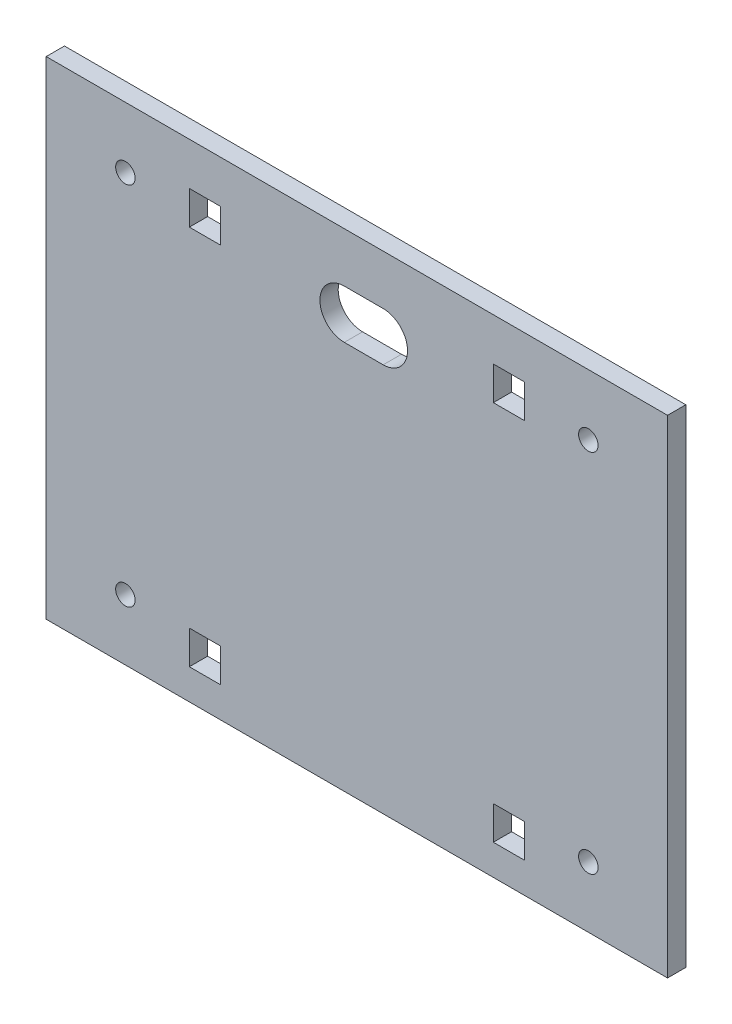
SolidWorks part; units mm, degrees
ref_plane "前视基准面" through (0, 0, 0) normal (0, 0, 1) x (1, 0, 0)
ref_plane "上视基准面" through (0, 0, 0) normal (0, 1, 0) x (1, 0, 0)
ref_plane "右视基准面" through (0, 0, 0) normal (1, 0, 0) x (0, 0, -1)
sketch "草图1" plane through (0, 0, 0) normal (0, 0, 1) x (1, 0, 0)
  line L1 (51, -25.25) -> (-51, -25.25)
  line L2 (51, -25.25) -> (51, -105.25)
  line L3 (51, -105.25) -> (-51, -105.25)
  line L4 (-51, -25.25) -> (-51, -105.25)
  circle A0 centre (-38, -35.25) radius 1.6
  circle A1 centre (-38, -95.25) radius 1.6
  circle A2 centre (38, -95.25) radius 1.6
  circle A3 centre (38, -35.25) radius 1.6
extrude "凸台-拉伸1" add sketch "草图1" along normal blind 3
sketch "草图3" plane through (0, 0, 3) normal (0, 0, 1) x (1, 0, 0)
  line L0 (-2.0655, -37.4152) -> (4.3184, -37.4152) construction
  line L1 (-2.0655, -33.4152) -> (4.3184, -33.4152)
  line L2 (-2.0655, -41.4152) -> (4.3184, -41.4152)
  arc A0 (-2.0655, -33.4152) -> (-2.0655, -41.4152) centre (-2.0655, -37.4152) ccw
  arc A1 (4.3184, -41.4152) -> (4.3184, -33.4152) centre (4.3184, -37.4152) ccw
  point P4 (1.1264, -37.4152)
  dimension "D1" = 4
extrude "切除-拉伸1" cut sketch "草图3" against normal blind 3
sketch "草图4" plane through (0, 0, 3) normal (0, 0, 1) x (1, 0, 0)
  line L0 (-27.5, -100.25) -> (-27.5, -92.8418) construction
  line L9 (-27.5, -94.75) -> (-22.4, -94.75)
  line L10 (-27.5, -94.75) -> (-27.5, -100.25)
  line L11 (-27.5, -100.25) -> (-22.4, -100.25)
  line L12 (-22.4, -94.75) -> (-22.4, -100.25)
  line L17 (-24.3668, -100.25) -> (-8.2877, -100.25) construction
  dimension "D1" = 5.1
  dimension "D2" = 5.5
extrude "切除-拉伸2" cut sketch "草图4" against normal blind 5
ref_plane "基准面1" through (0, 0, 0) normal (-1, 0, 0) x (0, 0, 1)
mirror "镜向1" about plane through (0, 0, 0) normal (-1, 0, 0) of "切除-拉伸2"
pattern_linear "阵列(线性)1" count 2 spacing 62.5 along (0, 1, 0) of "切除-拉伸2", "镜向1"
